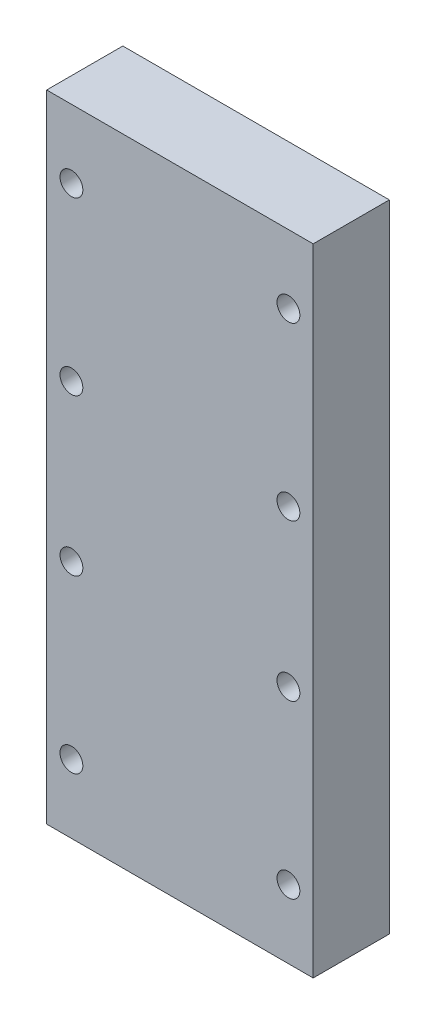
SolidWorks part; units mm, degrees
ref_plane "Piano frontale" through (0, 0, 0) normal (0, 0, 1) x (1, 0, 0)
ref_plane "Piano superiore" through (0, 0, 0) normal (0, 1, 0) x (1, 0, 0)
ref_plane "Piano destro" through (0, 0, 0) normal (1, 0, 0) x (0, 0, -1)
sketch "Schizzo1" plane through (0, 0, 0) normal (0, 0, 1) x (1, 0, 0)
  line L1 (35, -83.5) -> (-35, -83.5)
  line L2 (35, -83.5) -> (35, 83.5)
  line L3 (35, 83.5) -> (-35, 83.5)
  line L4 (-35, -83.5) -> (-35, 83.5)
  line L5 (35, -83.5) -> (-35, 83.5) construction
  line L6 (35, 83.5) -> (-35, -83.5) construction
  point P0 (0, 0)
  dimension "D1" = 167
  dimension "D2" = 70
extrude "Estrusione-Estrusione1" add sketch "Schizzo1" along normal blind 20
sketch "Schizzo2" plane through (0, 0, 0) normal (0, 0, -1) x (-1, 0, 0)
  circle A0 centre (-28.5, 65.5) radius 3 construction
  circle A1 centre (28.5, 65.5) radius 3 construction
  circle A2 centre (-28.5, 65.5) radius 3
  circle A3 centre (28.5, 65.5) radius 3
  circle A4 centre (-28.5, 20.5) radius 3 construction
  circle A5 centre (28.5, 20.5) radius 3 construction
  circle A6 centre (-28.5, 20.5) radius 3
  circle A7 centre (28.5, 20.5) radius 3
  circle A8 centre (-28.5, -20.5) radius 3 construction
  circle A9 centre (28.5, -20.5) radius 3 construction
  circle A10 centre (-28.5, -20.5) radius 3
  circle A11 centre (28.5, -20.5) radius 3
  circle A12 centre (-28.5, -65.5) radius 3 construction
  circle A13 centre (28.5, -65.5) radius 3 construction
  circle A14 centre (-28.5, -65.5) radius 3
  circle A15 centre (28.5, -65.5) radius 3
extrude "Taglio-Estrusione1" cut sketch "Schizzo2" against normal up to vertex (20 mm away)
